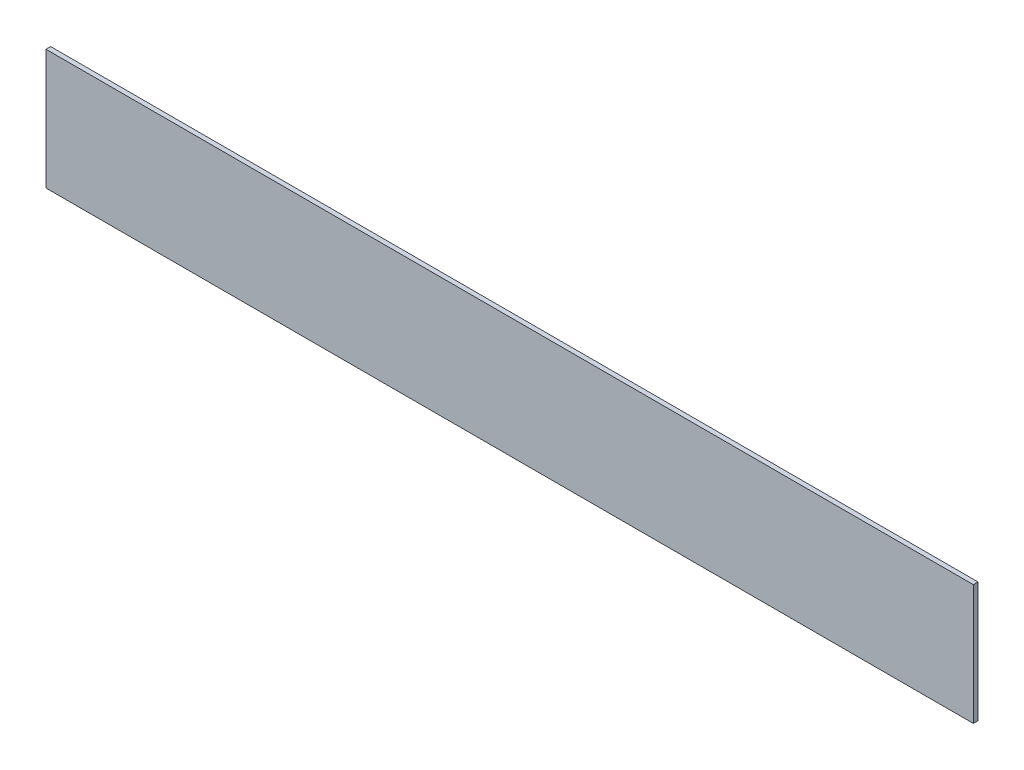
SolidWorks part; units mm, degrees
ref_plane "Płaszczyzna przednia" through (0, 0, 0) normal (0, 0, 1) x (1, 0, 0)
ref_plane "Płaszczyzna górna" through (0, 0, 0) normal (0, 1, 0) x (1, 0, 0)
ref_plane "Płaszczyzna prawa" through (0, 0, 0) normal (1, 0, 0) x (0, 0, -1)
sketch "Szkic1" plane through (0, 0, 0) normal (0, 0, 1) x (1, 0, 0)
  line L1 (-248.0845, -204.0748) -> (345.9155, -204.0748)
  line L2 (-248.0845, -204.0748) -> (-248.0845, -281.0748)
  line L3 (-248.0845, -281.0748) -> (345.9155, -281.0748)
  line L4 (345.9155, -204.0748) -> (345.9155, -281.0748)
  dimension "D1" = 594
  dimension "D2" = 77
extrude "Dodanie-wyciągnięcie1" add sketch "Szkic1" along normal blind 3
